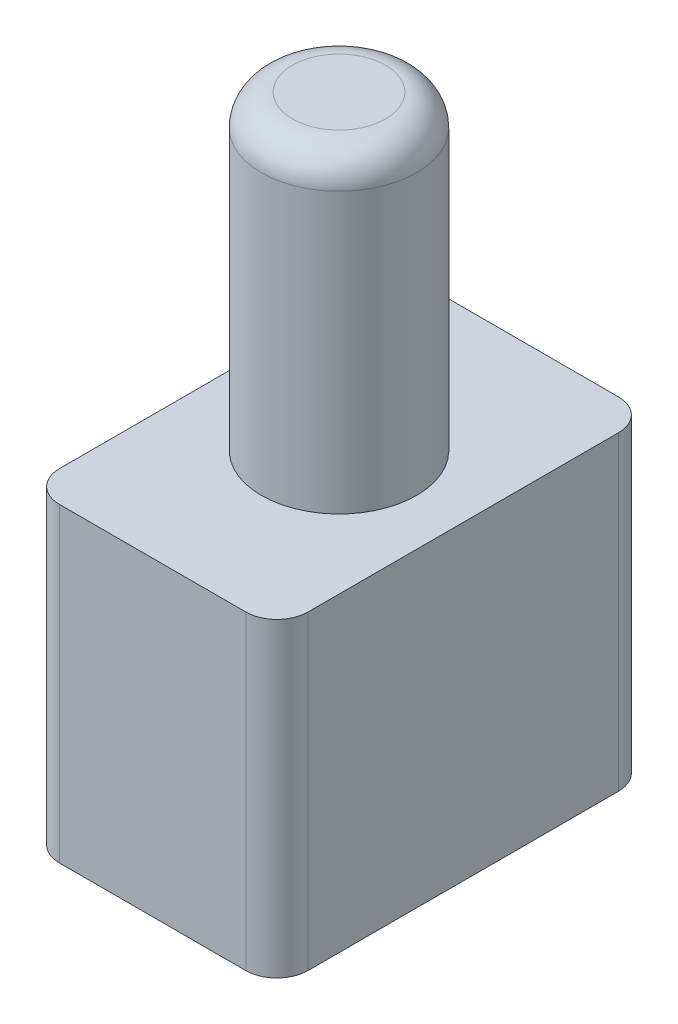
SolidWorks part; units mm, degrees
ref_plane "Front Plane" through (0, 0, 0) normal (0, 0, 1) x (1, 0, 0)
ref_plane "Top Plane" through (0, 0, 0) normal (0, 1, 0) x (1, 0, 0)
ref_plane "Right Plane" through (0, 0, 0) normal (1, 0, 0) x (0, 0, -1)
sketch "Sketch1" plane through (0, 0, 0) normal (0, 1, 0) x (1, 0, 0)
  line L1 (0, 0) -> (8, 0)
  line L2 (0, 0) -> (0, 12)
  line L3 (0, 12) -> (8, 12)
  line L4 (8, 0) -> (8, 12)
  dimension "D1" = 12
  dimension "D2" = 8
extrude "Boss-Extrude1" add sketch "Sketch1" along normal blind 10
sketch "Sketch2" plane through (0, 10, 0) normal (0, 1, 0) x (1, 0, 0)
  line L0 (0, 0) -> (8, 12) construction
  line L1 (0, 0) -> (8, 0) construction
  circle A0 centre (4, 6) radius 2.5
  dimension "D1" = 5
extrude "Boss-Extrude2" add sketch "Sketch2" along normal blind 10
fillet "Fillet1" radius 1 1 edges at (4, 20, -3.5)
fillet "Fillet2" radius 1 4 edges at (8, 5, -12) (0, 5, -12) (8, 5, 0) (0, 5, 0)
